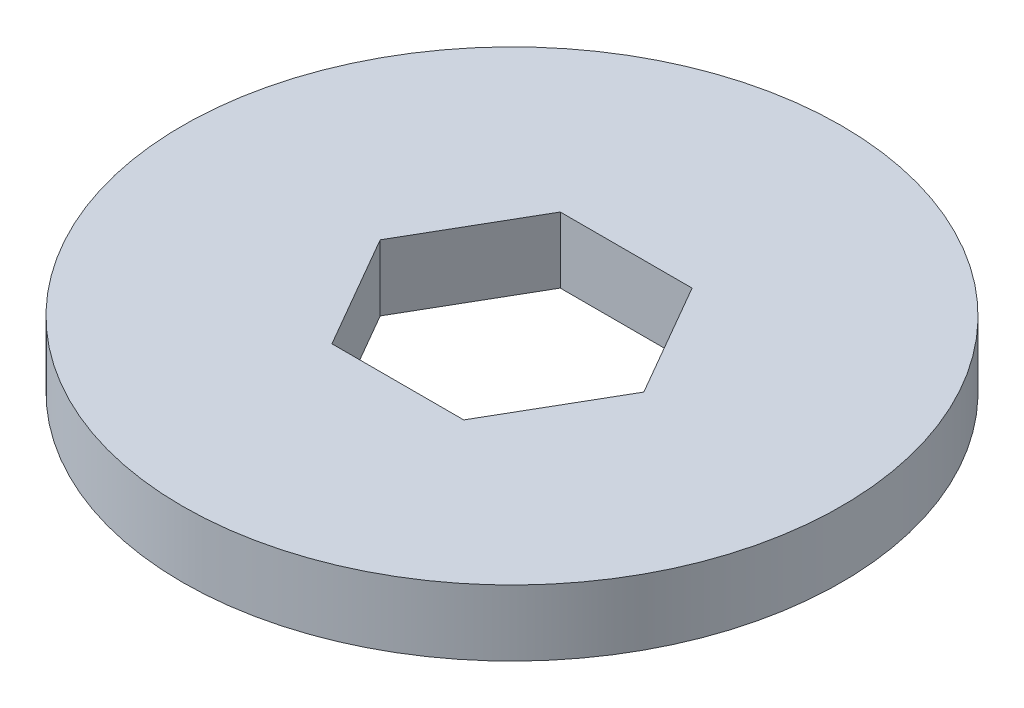
SolidWorks part; units mm, degrees
ref_plane "Front Plane" through (0, 0, 0) normal (0, 0, 1) x (1, 0, 0)
ref_plane "Top Plane" through (0, 0, 0) normal (0, 1, 0) x (1, 0, 0)
ref_plane "Right Plane" through (0, 0, 0) normal (1, 0, 0) x (0, 0, -1)
sketch "Sketch1" plane through (0, 0, 0) normal (0, 1, 0) x (1, 0, 0)
  line L1 (4, 0) -> (2, 3.4641)
  line L2 (2, 3.4641) -> (-2, 3.4641)
  line L3 (-2, 3.4641) -> (-4, 0)
  line L4 (-4, 0) -> (-2, -3.4641)
  line L5 (-2, -3.4641) -> (2, -3.4641)
  line L6 (2, -3.4641) -> (4, 0)
  circle A0 centre (0, 0) radius 3.4641 construction
  circle A1 centre (0, 0) radius 10
  circle A2 centre (0, 0) radius 4 construction
  dimension "D1" = 8
  dimension "D2" = 20
extrude "Boss-Extrude1" add sketch "Sketch1" along normal blind 2
